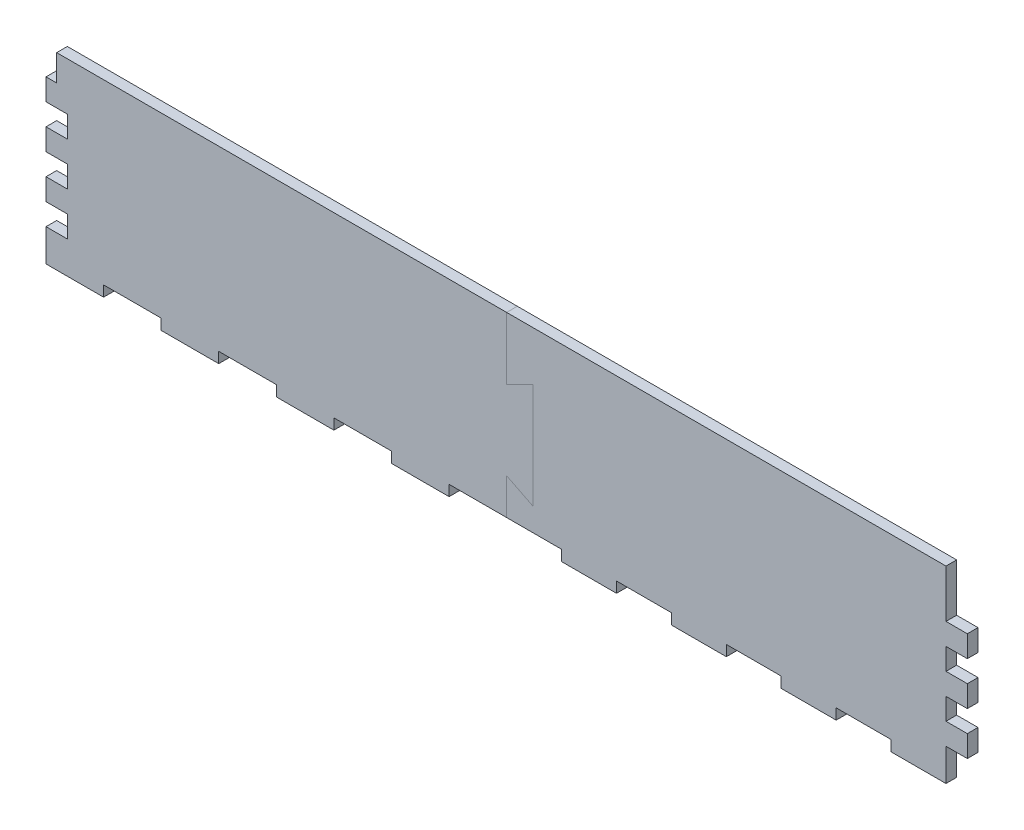
SolidWorks part; units mm, degrees
ref_plane "Front Plane" through (0, 0, 0) normal (0, 0, 1) x (1, 0, 0)
ref_plane "Top Plane" through (0, 0, 0) normal (0, 1, 0) x (1, 0, 0)
ref_plane "Right Plane" through (0, 0, 0) normal (1, 0, 0) x (0, 0, -1)
sketch "Sketch1" plane through (0, 0, 0) normal (0, 0, 1) x (1, 0, 0)
  line L0 (441.325, 0) -> (441.325, 73.025) construction
  line L1 (0, 0) -> (444.5, 0)
  line L2 (0, 0) -> (0, 73.025)
  line L3 (0, 73.025) -> (444.5, 73.025)
  line L4 (444.5, 0) -> (444.5, 73.025)
  line L5 (3.175, 0) -> (3.175, 73.025) construction
  dimension "D1" = 3.175
  dimension "D2" = 3.175
  dimension "D3" = 438.15
  dimension "D4" = 73.025
extrude "Boss-Extrude1" add sketch "Sketch1" along normal blind 5.15
sketch "Sketch3" plane through (0, 0, 0) normal (0, 0, -1) x (-1, 0, 0)
  line L0 (0, 0) -> (-444.5, 0) construction
  line L1 (-444.5, 73.025) -> (-441.325, 73.025)
  line L2 (-444.5, 73.025) -> (-444.5, 0)
  line L3 (-444.5, 0) -> (-441.325, 0)
  line L4 (-441.325, 73.025) -> (-441.325, 0)
  line L6 (0, 73.025) -> (-3.175, 73.025)
  line L7 (0, 73.025) -> (0, 0)
  line L8 (0, 0) -> (-3.175, 0)
  line L9 (-3.175, 73.025) -> (-3.175, 0)
  dimension "D1" = 3.175
extrude "Boss-Extrude2" add sketch "Sketch3" along normal blind 441.325
sketch "Sketch4" plane through (3.175, 0, 0) normal (1, 0, 0) x (0, 0, -1)
  line L0 (441.325, 73.025) -> (0, 73.025) construction
  line L1 (441.325, 0) -> (438.15, 0)
  line L2 (441.325, 0) -> (441.325, 73.025)
  line L3 (441.325, 73.025) -> (438.15, 73.025)
  line L4 (438.15, 0) -> (438.15, 73.025)
  dimension "D1" = 3.175
extrude "Boss-Extrude3" add sketch "Sketch4" along normal up to surface (438.15 mm away) up to face at (441.325, 36.5125, -220.6625)
sketch "Sketch5" plane through (0, 0, 5.15) normal (0, 0, -1) x (-1, 0, 0)
  line L0 (-444.5, 73.025) -> (0, 73.025) construction
  line L15 (-222.25, 73.025) -> (-222.25, 55.5625)
  line L16 (-222.25, 55.5625) -> (-234.95, 61.9125)
  line L17 (-234.95, 61.9125) -> (-234.95, 11.1125)
  line L18 (-234.95, 11.1125) -> (-222.25, 17.4625)
  line L19 (-222.25, 17.4625) -> (-222.25, 0)
  line L20 (0, 0) -> (-444.5, 0) construction
  line L21 (-234.95, 36.5125) -> (-444.5, 36.5125) construction
  line L22 (-444.5, 0) -> (-444.5, 73.025) construction
  point P0 (-222.25, 73.025)
  dimension "D1" = 12.7
  dimension "D2" = 50.8
  dimension "D3" = 6.35
split "Split2" trim tools "Sketch5" bodies to split 106 resulting bodies 107 108
sketch "Sketch8" plane through (444.5, 0, 0) normal (1, 0, 0) x (0, 0, -1)
  line L0 (-5.15, 73.025) -> (441.325, 73.025) construction
  line L1 (0, 73.025) -> (441.325, 73.025)
  line L2 (0, 73.025) -> (0, 0)
  line L3 (0, 0) -> (441.325, 0)
  line L4 (441.325, 73.025) -> (441.325, 0)
  line L5 (0, 0) -> (0, 73.025) construction
extrude "Cut-Extrude2" cut sketch "Sketch8" against normal through all
sketch "Sketch9" plane through (0, 0, 0) normal (0, 0, -1) x (-1, 0, 0)
  line L0 (0, 73.025) -> (0, 0) construction
  line L1 (0, 73.025) -> (-10.3, 73.025)
  line L2 (0, 73.025) -> (0, 62.5929)
  line L3 (0, 62.5929) -> (-10.3, 62.5929)
  line L4 (-10.3, 73.025) -> (-10.3, 62.5929)
  line L5 (0, 52.1607) -> (-10.3, 52.1607)
  line L6 (0, 52.1607) -> (0, 41.7286)
  line L7 (0, 41.7286) -> (-10.3, 41.7286)
  line L8 (-10.3, 52.1607) -> (-10.3, 41.7286)
  line L9 (-10.3, 10.4321) -> (-10.3, 20.8643) construction
  line L10 (0, 0) -> (-10.3, 0)
  line L11 (0, 0) -> (0, 10.4321)
  line L12 (0, 10.4321) -> (-10.3, 10.4321)
  line L13 (-10.3, 0) -> (-10.3, 10.4321)
  line L14 (0, 20.8643) -> (-10.3, 20.8643)
  line L15 (0, 20.8643) -> (0, 31.2964)
  line L16 (0, 31.2964) -> (-10.3, 31.2964)
  line L17 (-10.3, 20.8643) -> (-10.3, 31.2964)
  line L18 (-10.3, 31.2964) -> (-10.3, 41.7286) construction
  line L19 (-10.3, 52.1607) -> (-10.3, 62.5929) construction
  line L20 (-10.3, 0) -> (-10.3, 73.025)
  line L21 (0, 0) -> (0, 73.025)
  line L23 (-222.25, 0) -> (-222.25, 17.4625) construction
  line L24 (-434.2, 52.1607) -> (-434.2, 62.5929) construction
  line L25 (-434.2, 31.2964) -> (-434.2, 41.7286) construction
  line L26 (-434.2, 10.4321) -> (-434.2, 20.8643) construction
  line L27 (-444.5, 0) -> (-444.5, 73.025)
  line L44 (-434.2, 0) -> (-434.2, 73.025)
  line L45 (-434.2, 20.8643) -> (-434.2, 31.2964)
  line L46 (-444.5, 31.2964) -> (-434.2, 31.2964)
  line L47 (-444.5, 20.8643) -> (-444.5, 31.2964)
  line L48 (-444.5, 20.8643) -> (-434.2, 20.8643)
  line L49 (-434.2, 0) -> (-434.2, 10.4321)
  line L50 (-444.5, 10.4321) -> (-434.2, 10.4321)
  line L51 (-444.5, 0) -> (-444.5, 10.4321)
  line L52 (-444.5, 0) -> (-434.2, 0)
  line L53 (-434.2, 52.1607) -> (-434.2, 41.7286)
  line L54 (-444.5, 41.7286) -> (-434.2, 41.7286)
  line L55 (-444.5, 52.1607) -> (-444.5, 41.7286)
  line L56 (-444.5, 52.1607) -> (-434.2, 52.1607)
  line L57 (-434.2, 73.025) -> (-434.2, 62.5929)
  line L58 (-444.5, 62.5929) -> (-434.2, 62.5929)
  line L59 (-444.5, 73.025) -> (-444.5, 62.5929)
  line L60 (-444.5, 73.025) -> (-434.2, 73.025)
  point P38 (-434.2, 10.4321)
  point P39 (0, 0)
  line M13 (-222.25, 73.025) -> (-444.5, 73.025)
  line M14 (-444.5, 73.025) -> (-444.5, 0)
  line M15 (-444.5, 0) -> (-222.25, 0)
  dimension "D1" = 10.3
extrude "Cut-Extrude3" cut sketch "Sketch9" against normal through all contours L58 L44 M14 M13 | L56 L27 L54 L44 | L27 L48 L44 L46 | L50 L27 L44 M15 | L5 L21 L3 L20 | L16 L21 L7 L20 | L12 L21 L14 L20
ref_plane "Plane1" through (222.25, 0, 0) normal (1, 0, 0) x (0, 1, 0)
sketch "Sketch15" plane through (0, 0, 0) normal (0, 0, -1) x (-1, 0, 0)
  line L0 (-222.25, 0) -> (-434.2, 0) construction
  line L1 (-434.2, 0) -> (-407.7062, 0)
  line L2 (-434.2, 0) -> (-434.2, -5.15)
  line L3 (-434.2, -5.15) -> (-407.7062, -5.15)
  line L4 (-407.7062, 0) -> (-407.7062, -5.15)
  line L5 (-381.2125, 0) -> (-354.7187, 0)
  line L6 (-381.2125, 0) -> (-381.2125, -5.15)
  line L7 (-381.2125, -5.15) -> (-354.7187, -5.15)
  line L8 (-354.7187, 0) -> (-354.7187, -5.15)
  line L9 (-275.2375, -5.15) -> (-301.7312, -5.15) construction
  line L10 (-328.225, 0) -> (-301.7312, 0)
  line L11 (-328.225, 0) -> (-328.225, -5.15)
  line L12 (-328.225, -5.15) -> (-301.7312, -5.15)
  line L13 (-301.7312, 0) -> (-301.7312, -5.15)
  line L14 (-275.2375, 0) -> (-248.7437, 0)
  line L15 (-275.2375, 0) -> (-275.2375, -5.15)
  line L16 (-275.2375, -5.15) -> (-248.7437, -5.15)
  line L17 (-248.7437, 0) -> (-248.7437, -5.15)
  line L18 (-328.225, -5.15) -> (-354.7187, -5.15) construction
  line L19 (-381.2125, -5.15) -> (-407.7062, -5.15) construction
  line L20 (-248.7437, -5.15) -> (-222.25, -5.15) construction
  line L22 (-222.25, 0) -> (-222.25, 17.4625) construction
  point P19 (0, 0)
  point P21 (0, 0)
  dimension "D1" = 5.15
extrude "Boss-Extrude6" add sketch "Sketch15" against normal up to surface (5.15 mm away) up to face at (374.975, 36.5125, 5.15)
sketch "Sketch16" plane through (0, 0, 0) normal (0, 0, -1) x (-1, 0, 0)
  line L0 (0, 0) -> (-222.25, 0) construction
  line L1 (0, 0) -> (-27.7812, 0)
  line L2 (0, 0) -> (0, -5.15)
  line L3 (0, -5.15) -> (-27.7812, -5.15)
  line L4 (-27.7812, 0) -> (-27.7812, -5.15)
  line L5 (-55.5625, 0) -> (-83.3438, 0)
  line L6 (-55.5625, 0) -> (-55.5625, -5.15)
  line L7 (-55.5625, -5.15) -> (-83.3438, -5.15)
  line L8 (-83.3438, 0) -> (-83.3438, -5.15)
  line L9 (-166.6875, -5.15) -> (-138.9062, -5.15) construction
  line L10 (-111.125, 0) -> (-138.9062, 0)
  line L11 (-111.125, 0) -> (-111.125, -5.15)
  line L12 (-111.125, -5.15) -> (-138.9062, -5.15)
  line L13 (-138.9062, 0) -> (-138.9062, -5.15)
  line L14 (-166.6875, 0) -> (-194.4688, 0)
  line L15 (-166.6875, 0) -> (-166.6875, -5.15)
  line L16 (-166.6875, -5.15) -> (-194.4688, -5.15)
  line L17 (-194.4688, 0) -> (-194.4688, -5.15)
  line L18 (-111.125, -5.15) -> (-83.3438, -5.15) construction
  line L19 (-55.5625, -5.15) -> (-27.7812, -5.15) construction
  line L20 (-194.4688, -5.15) -> (-222.25, -5.15) construction
  line L22 (-275.2375, -5.15) -> (-248.7437, -5.15) construction
  line L24 (-222.25, 0) -> (-222.25, 17.4625) construction
  point P20 (0, 0)
  point P21 (0, 0)
  point P28 (0, 0)
extrude "Boss-Extrude7" add sketch "Sketch16" against normal up to surface (5.15 mm away) up to face at (71.035, 36.5125, 5.15)
sketch "Sketch17" plane through (0, 0, 0) normal (0, 0, -1) x (-1, 0, 0)
  line L1 (-434.2, 73.025) -> (-222.25, 73.025)
  line L2 (-434.2, 73.025) -> (-434.2, 85.725)
  line L3 (-434.2, 85.725) -> (-222.25, 85.725)
  line L4 (-222.25, 73.025) -> (-222.25, 85.725)
  point P4 (-222.25, 73.025)
  dimension "D1" = 12.7
extrude "Boss-Extrude8" add sketch "Sketch17" against normal up to surface (5.15 mm away)
sketch "Sketch18" plane through (0, 0, 0) normal (0, 0, -1) x (-1, 0, 0)
  line L0 (-222.25, 73.025) -> (0, 73.025) construction
  line L1 (-5.15, 73.025) -> (-222.25, 73.025)
  line L2 (-5.15, 73.025) -> (-5.15, 85.725)
  line L3 (-5.15, 85.725) -> (-222.25, 85.725)
  line L4 (-222.25, 73.025) -> (-222.25, 85.725)
  line L5 (0, 73.025) -> (0, 62.5929) construction
  point P4 (0, 73.025)
  point P5 (-8.2061, 73.025)
  dimension "D1" = 5.15
extrude "Boss-Extrude9" add sketch "Sketch18" against normal up to surface (5.15 mm away) up to face at (87.5426, 20.2662, 5.15)
equation "\"standard_thickness\"= 5.15mm"
equation "\"D1@Sketch18\"=\"standard_thickness\""
